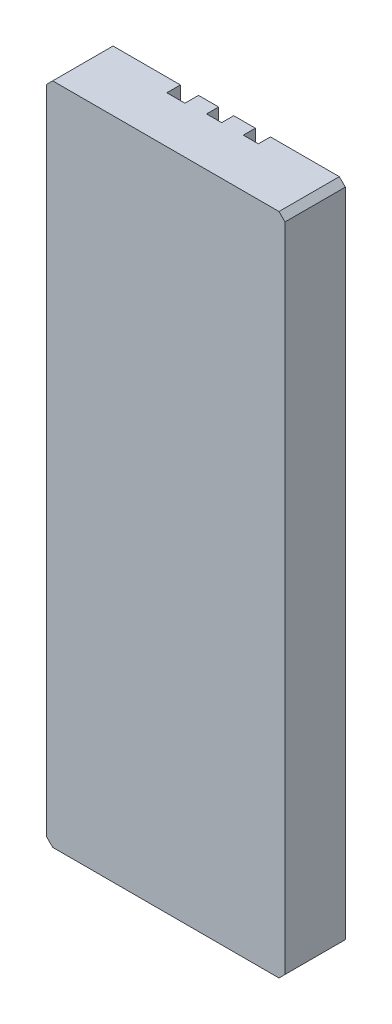
SolidWorks part; units mm, degrees
ref_plane "Front Plane" through (0, 0, 0) normal (0, 0, 1) x (1, 0, 0)
ref_plane "Top Plane" through (0, 0, 0) normal (0, 1, 0) x (1, 0, 0)
ref_plane "Right Plane" through (0, 0, 0) normal (1, 0, 0) x (0, 0, -1)
sketch "Sketch1" plane through (0, 0, 0) normal (0, 0, 1) x (1, 0, 0)
  line L0 (-59.5, -49) -> (17.5, -49) construction
  line L1 (18.5, -59) -> (-60.5, -59)
  line L2 (18.5, -59) -> (18.5, -279)
  line L3 (18.5, -279) -> (-60.5, -279)
  line L4 (-60.5, -59) -> (-60.5, -279)
  line L6 (18.5, -48) -> (18.5, 4) construction
  dimension "D1" = 10
  dimension "D2" = 79
  dimension "D3" = 220
extrude "Boss-Extrude1" add sketch "Sketch1" against normal blind 20
sketch "Sketch2" plane through (0, -59, 0) normal (0, 1, 0) x (1, 0, 0)
  line L1 (-36.1667, 21.5) -> (-30.1667, 21.5)
  line L2 (-36.1667, 21.5) -> (-36.1667, 15.5)
  line L3 (-36.1667, 15.5) -> (-30.1667, 15.5)
  line L4 (-30.1667, 21.5) -> (-30.1667, 15.5)
  line L5 (-36.1667, 21.5) -> (-30.1667, 15.5) construction
  line L6 (-36.1667, 15.5) -> (-30.1667, 21.5) construction
  point P0 (-33.1667, 18.5)
  dimension "D1" = 6
  dimension "D2" = 6
extrude "Cut-Extrude1" cut sketch "Sketch2" against normal blind 76
sketch "Sketch3" plane through (0, -59, 0) normal (0, 1, 0) x (1, 0, 0)
  line L1 (-23.5017, 21) -> (-18.5017, 21)
  line L2 (-23.5017, 21) -> (-23.5017, 16)
  line L3 (-23.5017, 16) -> (-18.5017, 16)
  line L4 (-18.5017, 21) -> (-18.5017, 16)
  line L5 (-23.5017, 21) -> (-18.5017, 16) construction
  line L6 (-23.5017, 16) -> (-18.5017, 21) construction
  point P0 (-21.0017, 18.5)
  dimension "D1" = 5
  dimension "D2" = 5
extrude "Cut-Extrude2" cut sketch "Sketch3" against normal blind 189
sketch "Sketch4" plane through (0, -59, 0) normal (0, 1, 0) x (1, 0, 0)
  line L1 (-6.335, 21) -> (-11.335, 21)
  line L2 (-6.335, 21) -> (-6.335, 16)
  line L3 (-6.335, 16) -> (-11.335, 16)
  line L4 (-11.335, 21) -> (-11.335, 16)
  line L5 (-6.335, 21) -> (-11.335, 16) construction
  line L6 (-6.335, 16) -> (-11.335, 21) construction
  point P0 (-8.835, 18.5)
  dimension "D1" = 5
  dimension "D2" = 5
extrude "Cut-Extrude3" cut sketch "Sketch4" against normal blind 100
sketch "Sketch5" plane through (0, 0, -20) normal (0, 0, -1) x (-1, 0, 0)
  line L0 (6.335, -59) -> (6.335, -159) construction
  line L1 (3.835, -158.997) -> (13.835, -158.997)
  line L2 (3.835, -158.997) -> (3.835, -133.997)
  line L3 (3.835, -133.997) -> (13.835, -133.997)
  line L4 (13.835, -158.997) -> (13.835, -133.997)
  line L5 (11.335, -159) -> (11.335, -59) construction
  dimension "D1" = 2.5
  dimension "D2" = 2.5
  dimension "D3" = 25
extrude "Cut-Extrude4" cut sketch "Sketch5" against normal up to surface (4 mm away) up to face at (-8.835, -109, -16)
fillet "Fillet1" radius 2 4 edges at (-3.835, -133.997, -18) (-13.835, -133.997, -18) (-3.835, -158.997, -18) (-13.835, -158.997, -18)
sketch "Sketch6" plane through (0, 0, -20) normal (0, 0, -1) x (-1, 0, 0)
  line L0 (36.1667, -135) -> (36.1667, -59) construction
  line L1 (27.6667, -135) -> (38.6667, -135)
  line L2 (27.6667, -135) -> (27.6667, -110)
  line L3 (27.6667, -110) -> (38.6667, -110)
  line L4 (38.6667, -135) -> (38.6667, -110)
  line L5 (30.1667, -59) -> (30.1667, -135) construction
  dimension "D1" = 2.5
  dimension "D2" = 2.5
  dimension "D3" = 25
extrude "Cut-Extrude5" cut sketch "Sketch6" against normal up to surface (4.5 mm away) up to face at (-33.1667, -97, -15.5)
fillet "Fillet2" radius 2 4 edges at (-38.6667, -110, -17.75) (-27.6667, -110, -17.75) (-27.6667, -135, -17.75) (-38.6667, -135, -17.75)
sketch "Sketch7" plane through (0, 0, -20) normal (0, 0, -1) x (-1, 0, 0)
  line L0 (25.0017, -261.5) -> (17.0017, -261.5) construction
  line L1 (28.0017, -234.5) -> (14.0017, -234.5)
  line L2 (28.0017, -234.5) -> (28.0017, -269.5)
  line L3 (28.0017, -269.5) -> (14.0017, -269.5)
  line L4 (14.0017, -234.5) -> (14.0017, -269.5)
  line L5 (25.0017, -261.5) -> (25.0017, -243) construction
  line L6 (17.0017, -261.5) -> (17.0017, -243) construction
  dimension "D1" = 8
  dimension "D2" = 3
  dimension "D3" = 3
  dimension "D4" = 35
extrude "Cut-Extrude6" cut sketch "Sketch7" against normal up to surface (4 mm away) up to face at (-21.0017, -153.5, -16)
fillet "Fillet3" radius 2 4 edges at (-28.0017, -234.5, -18) (-14.0017, -234.5, -18) (-14.0017, -269.5, -18) (-28.0017, -269.5, -18)
chamfer "Chamfer1" distance 2 angle 45 4 edges at (-60.5, -59, -10) (18.5, -59, -10) (-60.5, -279, -10) (18.5, -279, -10)
